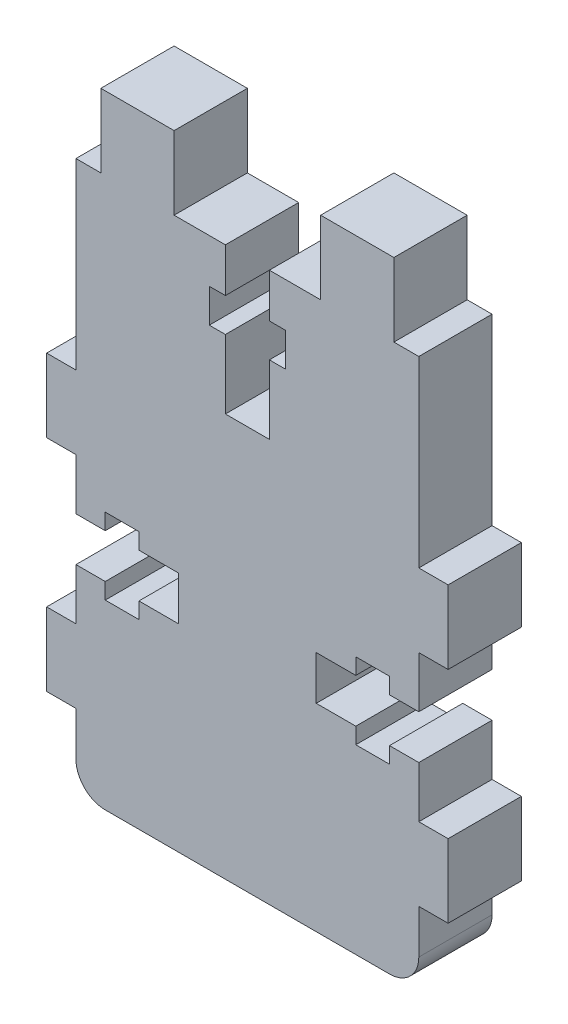
SolidWorks part; units mm, degrees
ref_plane "Plan de face" through (0, 0, 0) normal (0, 0, 1) x (1, 0, 0)
ref_plane "Plan de dessus" through (0, 0, 0) normal (0, 1, 0) x (1, 0, 0)
ref_plane "Plan de droite" through (0, 0, 0) normal (1, 0, 0) x (0, 0, -1)
sketch "Esquisse1" plane through (0, 0, 0) normal (0, 0, 1) x (1, 0, 0)
  line L0 (0, 0) -> (0, 37.5) construction
  line L1 (0, 37.5) -> (23.4, 37.5) construction
  line L2 (23.4, 37.5) -> (23.4, 0) construction
  line L3 (23.4, 0) -> (0, 0) construction
  line L4 (0, 15) -> (23.4, 15) construction
  line L5 (1.7, 37.5) -> (0, 37.5)
  line L6 (0, 37.5) -> (0, 25)
  line L7 (21.7, 37.5) -> (23.4, 37.5)
  line L8 (23.4, 37.5) -> (23.4, 25)
  line L9 (23.4, 5) -> (23.4, 0)
  line L10 (0, 0) -> (23.4, 0)
  line L12 (0, 0) -> (0, 5)
  line B0 (9.1, 34.5) -> (9.1, 32.2)
  line B1 (13.2, 32.2) -> (13.2, 27.5)
  line B2 (10.2, 27.5) -> (10.2, 32.2)
  line B3 (9.1, 32.2) -> (10.2, 32.2)
  line B4 (11.7, 37.5) -> (11.7, 26.2792) construction
  line B5 (10.2, 37.5) -> (6.7, 37.5)
  line B6 (6.7, 42.5) -> (1.7, 42.5)
  line B7 (1.7, 42.5) -> (1.7, 37.5)
  line B8 (6.7, 42.5) -> (6.7, 37.5)
  line B9 (13.2, 37.5) -> (16.7, 37.5)
  line B10 (16.7, 37.5) -> (16.7, 42.5)
  line B11 (16.7, 42.5) -> (21.7, 42.5)
  line B12 (21.7, 42.5) -> (21.7, 37.5)
  line B13 (10.2, 37.5) -> (13.2, 37.5) construction
  line B14 (13.2, 37.5) -> (13.2, 34.5)
  line B15 (13.2, 32.2) -> (14.3, 32.2)
  line B16 (14.3, 34.5) -> (13.2, 34.5)
  line B17 (13.2, 27.5) -> (10.2, 27.5)
  line B18 (10.2, 34.5) -> (9.1, 34.5)
  line B19 (14.3, 32.2) -> (14.3, 34.5)
  line B20 (10.2, 34.5) -> (10.2, 37.5)
  line B21 (11.7, 27.5) -> (11.7, 37.5) construction
  line B22 (23.3419, 15) -> (9.4468, 15) construction
  line B23 (23.4, 13.5) -> (23.4, 10)
  line B24 (25.4, 10) -> (25.4, 5)
  line B25 (25.4, 5) -> (23.4, 5)
  line B26 (25.4, 10) -> (23.4, 10)
  line B27 (23.4, 16.2928) -> (23.4, 20)
  line B28 (23.4, 20) -> (25.4, 20)
  line B29 (25.4, 20) -> (25.4, 25)
  line B30 (25.4, 25) -> (23.4, 25)
  line B31 (23.4, 13.5) -> (23.4, 16.5) construction
  line B32 (23.4, 16.5) -> (21.4, 16.5)
  line B33 (19.1, 16.5) -> (19.1, 17.6)
  line B34 (21.4, 12.4) -> (19.1, 12.4)
  line B35 (21.4, 17.6) -> (21.4, 16.5)
  line B36 (19.1, 16.5) -> (16.4, 16.5)
  line B37 (16.4, 16.5) -> (16.4, 13.5)
  line B38 (16.4, 13.5) -> (19.1, 13.5)
  line B39 (21.4, 13.5) -> (21.4, 12.4)
  line B40 (19.1, 17.6) -> (21.4, 17.6)
  line B41 (19.1, 12.4) -> (19.1, 13.5)
  line B42 (21.4, 13.5) -> (23.4, 13.5)
  line B43 (16.4, 15) -> (23.4, 15) construction
  line B44 (0.0581, 15) -> (13.9532, 15) construction
  line B45 (0, 13.5) -> (0, 10)
  line B46 (-2, 10) -> (-2, 5)
  line B47 (-2, 5) -> (0, 5)
  line B48 (-2, 10) -> (0, 10)
  line B49 (0, 16.2928) -> (0, 20)
  line B50 (0, 20) -> (-2, 20)
  line B51 (-2, 20) -> (-2, 25)
  line B52 (-2, 25) -> (0, 25)
  line B53 (0, 13.5) -> (0, 16.5) construction
  line B54 (0, 16.5) -> (2, 16.5)
  line B55 (4.3, 16.5) -> (4.3, 17.6)
  line B56 (2, 12.4) -> (4.3, 12.4)
  line B57 (2, 17.6) -> (2, 16.5)
  line B58 (4.3, 16.5) -> (7, 16.5)
  line B59 (7, 16.5) -> (7, 13.5)
  line B60 (7, 13.5) -> (4.3, 13.5)
  line B61 (2, 13.5) -> (2, 12.4)
  line B62 (4.3, 17.6) -> (2, 17.6)
  line B63 (4.3, 12.4) -> (4.3, 13.5)
  line B64 (2, 13.5) -> (0, 13.5)
  line B65 (7, 15) -> (0, 15) construction
  dimension "D1" = 23.4
  dimension "D2" = 15
  dimension "D3" = 22.5
sketch_block_instance "Insert M3 plots ep 5mm-13"
sketch_block "Insert M3 plots ep 5mm" parameters "D1"=10, "D2"=5, "D3"=5
sketch_block_instance "Decoupe Insert M3-4"
sketch_block "Decoupe Insert M3" parameters "D1"=5.2, "D2"=3, "D3"=2.3, "D4"=3, "D5"=10
sketch_block_instance "Bloc1-1"
sketch_block "Bloc1" parameters "D1"=10, "D2"=5, "D3"=2
sketch_block_instance "Bloc3-3"
sketch_block "Bloc3" parameters "D1"=5.2, "D2"=3, "D3"=2.3, "D4"=2, "D5"=7
sketch_block_instance "Bloc1-3"
extrude "Boss.-Extru.1" add sketch "Esquisse1" along normal blind 5
fillet "Fillet1" radius 2 2 edges at (0, 0, 2.5) (23.4, 0, 2.5)
